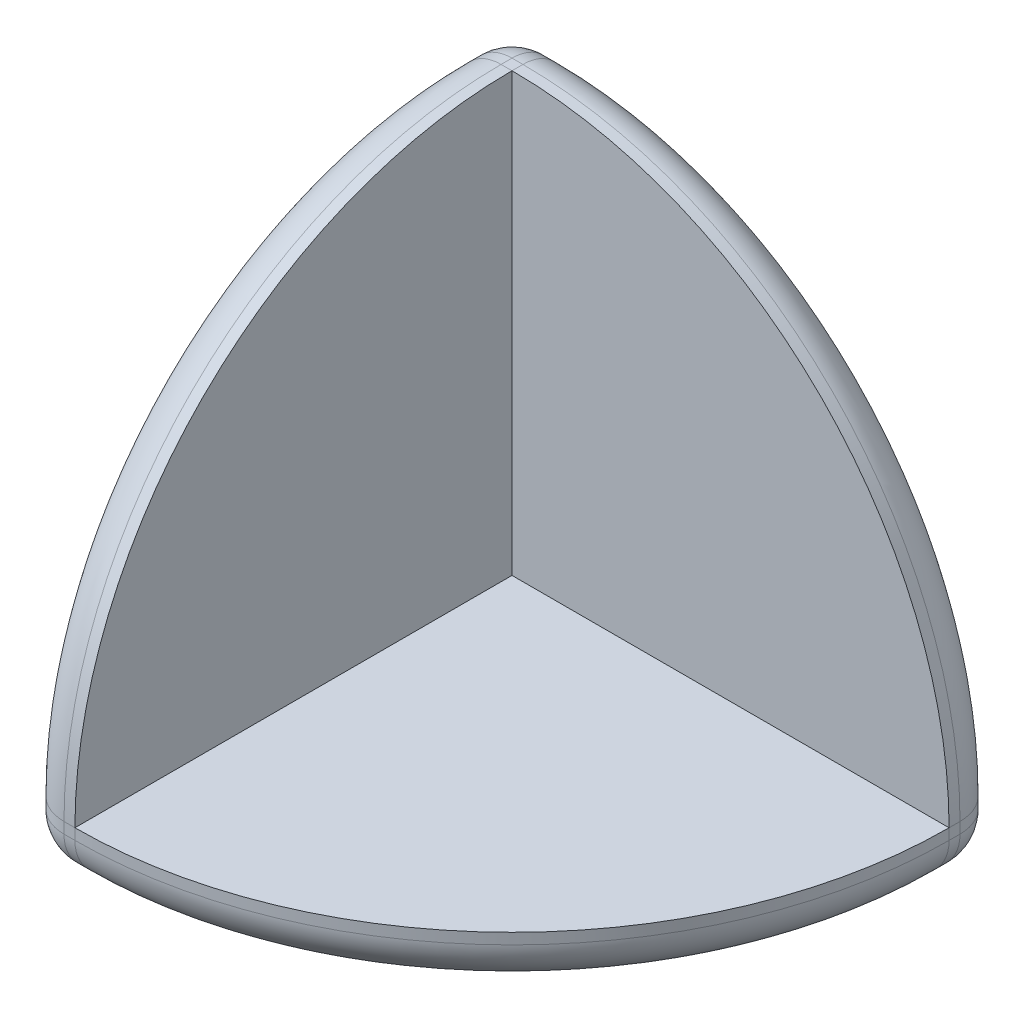
SolidWorks part; units mm, degrees
ref_plane "Front Plane" through (0, 0, 0) normal (0, 0, 1) x (1, 0, 0)
ref_plane "Top Plane" through (0, 0, 0) normal (0, 1, 0) x (1, 0, 0)
ref_plane "Right Plane" through (0, 0, 0) normal (1, 0, 0) x (0, 0, -1)
sketch "Sketch1" plane through (0, 0, 0) normal (0, 0, 1) x (1, 0, 0)
  line L0 (0, 0) -> (0, 25.4)
  line L1 (0, 0) -> (25.4, 0)
  line L2 (0, 25.4) -> (-3.175, 25.4)
  line L3 (-3.175, 25.4) -> (-3.175, -3.175)
  line L4 (-3.175, -3.175) -> (25.4, -3.175)
  line L5 (25.4, -3.175) -> (25.4, 0)
  arc A0 (25.4, 0) -> (0, 25.4) centre (0, 0) ccw
  dimension "D1" = 25.4
  dimension "D2" = 3.175
  dimension "D3" = 3.175
extrude "Boss-Extrude1" add sketch "Sketch1" along normal blind 3.175 contours L4 L5 L1 L0 L2 L3 | L1 A0 L0
sketch "Sketch2" plane through (-3.175, 0, 0) normal (-1, 0, 0) x (0, 0, 1)
  line L0 (3.175, 25.4) -> (3.175, 0)
  line L1 (3.175, 25.4) -> (3.175, -3.175) construction
  line L2 (3.175, 0) -> (28.575, 0)
  line L3 (28.575, 0) -> (28.575, -3.175)
  line L4 (28.575, -3.175) -> (3.175, -3.175)
  line L5 (3.175, 0) -> (3.175, -3.175)
  arc A0 (28.575, 0) -> (3.175, 25.4) centre (3.175, 0) ccw
  line M3 (3.175, -3.175) -> (3.175, 25.4)
  dimension "D2" = 3.175
extrude "Boss-Extrude2" add sketch "Sketch2" against normal blind 3.175 contours L4 L3 L2 M3 | L2 A0 M3
sketch "Sketch5" plane through (0, -3.175, 0) normal (0, -1, 0) x (1, 0, 0)
  line L0 (0, 28.575) -> (0, 3.175) construction
  line L1 (0, 3.175) -> (25.4, 3.175) construction
  line L2 (0, 28.575) -> (0, 3.175)
  line L3 (0, 3.175) -> (25.4, 3.175)
  arc A0 (25.4, 3.175) -> (0, 28.575) centre (0, 3.175) ccw
extrude "Boss-Extrude3" add sketch "Sketch5" against normal blind 3.175
fillet "Fillet1" radius 2.54 12 edges at (-3.175, -1.5875, 28.575) (-3.175, 25.4, 1.5875) (25.4, -3.175, 1.5875) (-1.5875, -3.175, 28.575) (25.4, -1.5875, 0) (-1.5875, 25.4, 0) (11.1125, -3.175, 0) (-3.175, 11.1125, 0) (-3.175, -3.175, 14.2875) (-3.175, 17.9605, 21.1355) (17.9605, -3.175, 21.1355) (17.9605, 17.9605, 0)
